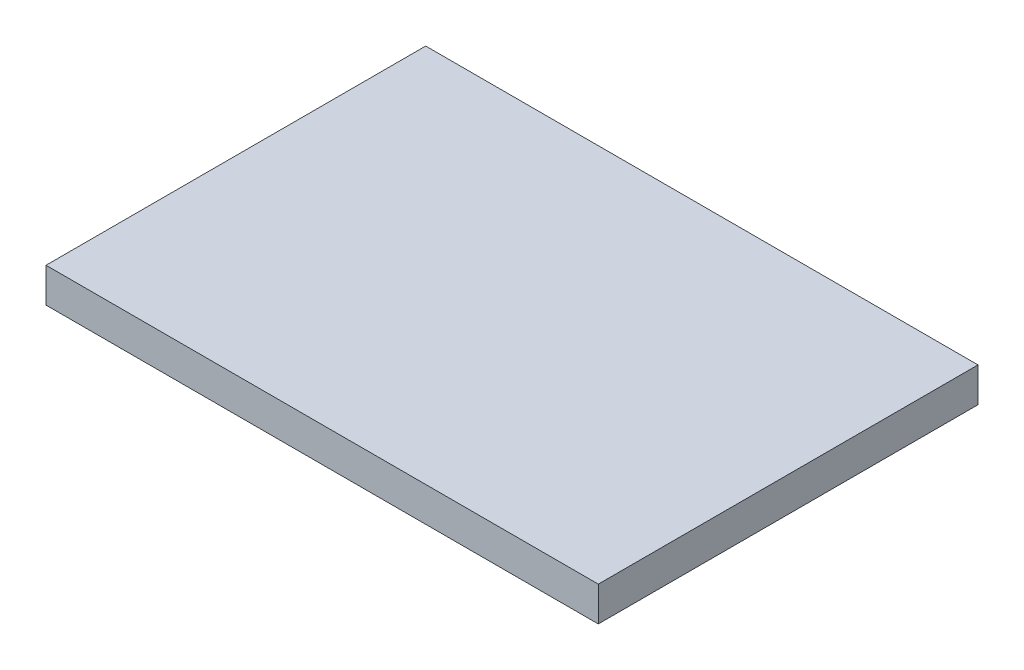
SolidWorks part; units mm, degrees
ref_plane "Front Plane" through (0, 0, 0) normal (0, 0, 1) x (1, 0, 0)
ref_plane "Top Plane" through (0, 0, 0) normal (0, 1, 0) x (1, 0, 0)
ref_plane "Right Plane" through (0, 0, 0) normal (1, 0, 0) x (0, 0, -1)
sketch "Sketch1" plane through (0, 0, 0) normal (0, 1, 0) x (1, 0, 0)
  line L1 (16, -11) -> (-16, -11)
  line L2 (16, -11) -> (16, 11)
  line L3 (16, 11) -> (-16, 11)
  line L4 (-16, -11) -> (-16, 11)
  line L5 (16, -11) -> (-16, 11) construction
  line L6 (16, 11) -> (-16, -11) construction
  point P0 (0, 0)
  dimension "D1" = 32
  dimension "D2" = 22
extrude "Boss-Extrude1" add sketch "Sketch1" along normal blind 2
